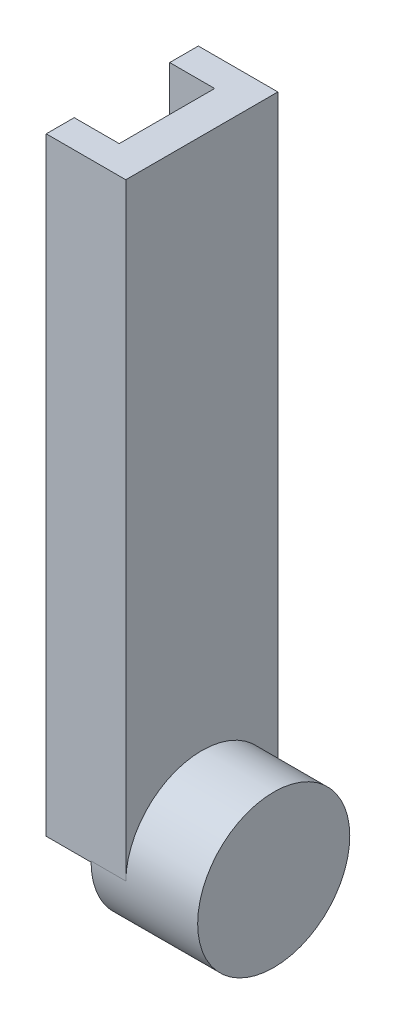
SolidWorks part; units mm, degrees
ref_plane "Front Plane" through (0, 0, 0) normal (0, 0, 1) x (1, 0, 0)
ref_plane "Top Plane" through (0, 0, 0) normal (0, 1, 0) x (1, 0, 0)
ref_plane "Right Plane" through (0, 0, 0) normal (1, 0, 0) x (0, 0, -1)
sketch "Sketch1" plane through (0, 0, 0) normal (1, 0, 0) x (0, 0, -1)
  circle A0 centre (0, 0) radius 10
  dimension "D1" = 20
extrude "Boss-Extrude7" add sketch "Sketch1" along normal blind 14
sketch "Sketch7" plane through (0, 0, 0) normal (0, 1, 0) x (1, 0, 0)
  line L0 (14, 10) -> (0, 10) construction
  line L1 (4.5459, 10) -> (-5.9133, 10)
  line L2 (4.5459, 10) -> (4.5459, -9.9991)
  line L3 (4.5459, -9.9991) -> (-5.9133, -9.9991)
  line L4 (-5.9133, 10) -> (-5.9133, -9.9991)
extrude "Boss-Extrude9" add sketch "Sketch7" along normal blind 80
sketch "Sketch8" plane through (0, 80, 0) normal (0, 1, 0) x (1, 0, 0)
  line L0 (-5.9133, 10) -> (-5.9133, -9.9991) construction
  line L1 (-5.9133, 6.2337) -> (0, 6.2337)
  line L2 (-5.9133, 6.2337) -> (-5.9133, -6.3174)
  line L3 (-5.9133, -6.3174) -> (0, -6.3174)
  line L4 (0, 6.2337) -> (0, -6.3174)
  dimension "D1" = 12.5511
  dimension "D2" = 5.9133
extrude "Cut-Extrude3" cut sketch "Sketch8" against normal blind 55
sketch "Sketch10" plane through (0, 0, 0) normal (-1, 0, 0) x (0, 0, 1)
  line L0 (6.3174, 25) -> (6.3174, 80) construction
  line L1 (-6.3174, 57.1527) -> (6.3174, 57.1527)
  line L2 (-6.3174, 57.1527) -> (-6.3174, 61.6711)
  line L3 (-6.3174, 61.6711) -> (6.3174, 61.6711)
  line L4 (6.3174, 57.1527) -> (6.3174, 61.6711)
  line L5 (-6.3174, 57.1527) -> (6.3174, 61.6711) construction
  line L6 (-6.3174, 61.6711) -> (6.3174, 57.1527) construction
  point P0 (0, 59.4119)
